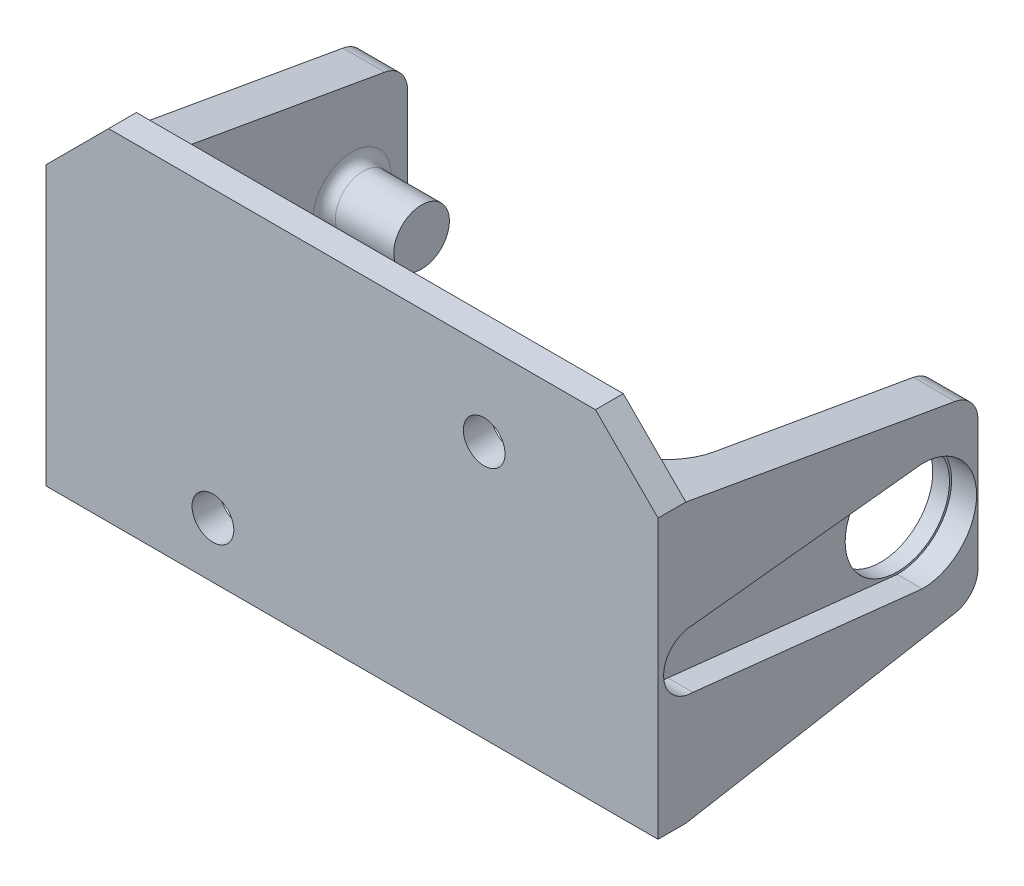
SolidWorks part; units mm, degrees
ref_plane "Front Plane" through (0, 0, 0) normal (0, 0, 1) x (1, 0, 0)
ref_plane "Top Plane" through (0, 0, 0) normal (0, 1, 0) x (1, 0, 0)
ref_plane "Right Plane" through (0, 0, 0) normal (1, 0, 0) x (0, 0, -1)
sketch "Sketch1" plane through (0, 0, 0) normal (0, 0, 1) x (1, 0, 0)
  line L1 (-19, -10) -> (19, -10)
  line L2 (-19, -10) -> (-19, 10)
  line L3 (-19, 10) -> (19, 10)
  line L4 (19, -10) -> (19, 10)
  line L5 (-19, -10) -> (19, 10) construction
  line L6 (-19, 10) -> (19, -10) construction
  point P0 (0, 0)
  dimension "D1" = 38
  dimension "D2" = 20
extrude "Boss-Extrude1" add sketch "Sketch1" along normal blind 2
sketch "Sketch2" plane through (19, 0, 0) normal (1, 0, 0) x (0, 0, -1)
  line L0 (-2, 10) -> (0, 10)
  line L1 (0, 10) -> (19.3473, 6.5885)
  line L2 (21, 4.6189) -> (21, -4.6189)
  line L3 (19.3473, -6.5885) -> (0, -10)
  line L4 (0, -10) -> (-2, -10)
  line L5 (-2, -10) -> (-2, 10)
  arc A0 (21, -4.6189) -> (19.3473, -6.5885) centre (19, -4.6189) cw
  arc A1 (19.3473, 6.5885) -> (21, 4.6189) centre (19, 4.6189) cw
  point P12 (21, -6.2971)
  dimension "D4" = 2
  dimension "D1" = 100
  dimension "D2" = 100
  dimension "D3" = 21
extrude "Boss-Extrude2" add sketch "Sketch2" along normal blind 3
mirror "Mirror1" about plane through (0, 0, 0) normal (1, 0, 0) of "Boss-Extrude2"
sketch "Sketch3" plane through (0, 0, 0) normal (0, 0, -1) x (-1, 0, 0)
  line L0 (-22, -10) -> (-17.5, -14.5)
  line L1 (-17.5, -14.5) -> (17.5, -14.5)
  line L2 (17.5, -14.5) -> (22, -10)
  line L3 (22, -10) -> (-22, -10)
  line L4 (-22, 10) -> (22, 10)
  line L5 (22, 10) -> (17.5, 14.5)
  line L6 (17.5, 14.5) -> (-17.5, 14.5)
  line L7 (-17.5, 14.5) -> (-22, 10)
  dimension "D1" = 45
  dimension "D2" = 45
  dimension "D3" = 45
  dimension "D4" = 45
  dimension "D5" = 35
  dimension "D6" = 35
extrude "Boss-Extrude3" add sketch "Sketch3" against normal blind 2
sketch "Sketch4" plane through (-22, 0, 0) normal (-1, 0, 0) x (0, 0, 1)
  line L0 (-21, -4.6189) -> (-21, 4.6189) construction
  circle A0 centre (-17, 0) radius 4
  circle A1 centre (-17, 0) radius 1.6
  dimension "D1" = 8
  dimension "D2" = 3.2
extrude "Cut-Extrude1" cut sketch "Sketch4" against normal through all contours A1
sketch "Sketch5" plane through (19, 0, 0) normal (-1, 0, 0) x (0, 0, 1)
  line L16 (-17, -3.9) -> (-0.5, -2.1)
  line L17 (-0.5, 2.1) -> (-17, 3.9)
  arc A2 (-17, 3.9) -> (-17, -3.9) centre (-17, 0) ccw
  arc A3 (-0.5, -2.1) -> (-0.5, 2.1) centre (-0.5, 0) ccw
  dimension "D1" = 7.8
  dimension "D2" = 4.2
  dimension "D3" = 16.5
extrude "Cut-Extrude2" cut sketch "Sketch5" against normal blind 2 from offset 1.2 offset against normal yes
sketch "Sketch6" plane through (19, 0, 0) normal (-1, 0, 0) x (0, 0, 1)
  circle A1 centre (-17, 0) radius 1.6 construction
  circle A2 centre (-17, 0) radius 3.75
  dimension "D1" = 7.5
extrude "Cut-Extrude3" cut sketch "Sketch6" against normal blind 2.4
sketch "Sketch7" plane through (0, 0, 0) normal (0, 0, -1) x (-1, 0, 0)
  line L0 (-22, 0) -> (22, 0)
  line L1 (22, 10) -> (-22, 10)
  line L2 (22, 10) -> (22, 16)
  line L3 (22, 16) -> (-22, 16)
  line L4 (-22, 10) -> (-22, 16)
  line L5 (-22, -4.6189) -> (-22, 4.6189) construction
  line L6 (22, -4.6189) -> (22, 4.6189) construction
  line L7 (22, -16) -> (-22, -16)
  line L8 (-22, -10) -> (-22, -16)
  line L9 (22, -10) -> (-22, -10)
  line L10 (22, -10) -> (22, -16)
  line M6 (-19, -10) -> (-22, -10)
  line M7 (-22, -10) -> (-17.5, -14.5)
  line M8 (-17.5, -14.5) -> (17.5, -14.5)
  line M9 (17.5, -14.5) -> (22, -10)
  line M10 (22, -10) -> (19, -10)
  dimension "D1" = 6
extrude "Cut-Extrude4" cut sketch "Sketch7" against normal through all contours L9 M10 M6 M7 M8 M9
sketch "Sketch8" plane through (-22, 0, 0) normal (-1, 0, 0) x (0, 0, 1)
  circle A0 centre (-17, 0) radius 1.6 construction
  circle A1 centre (-17, 0) radius 1.6 construction
  circle A2 centre (-17, 0) radius 2
  dimension "D1" = 4
extrude "Boss-Extrude4" add sketch "Sketch8" against normal blind 8
fillet "Fillet1" radius 0.8 1 edges at (-19, 0, -19)
fillet "Fillet2" radius 5 2 edges
sketch "Sketch9" plane through (0, 0, 0) normal (0, 0, -1) x (-1, 0, 0)
  line L0 (17.5, 14.5) -> (-17.5, 14.5) construction
  line L1 (14, -10) -> (-14, -10) construction
  circle A0 centre (-9.5, 8.5) radius 1.5
  circle A1 centre (10, -6) radius 1.5
  dimension "D1" = 3
  dimension "D2" = 3
  dimension "D3" = 8
  dimension "D4" = 6
  dimension "D5" = 4
  dimension "D6" = 12
extrude "Cut-Extrude5" cut sketch "Sketch9" against normal blind 10
